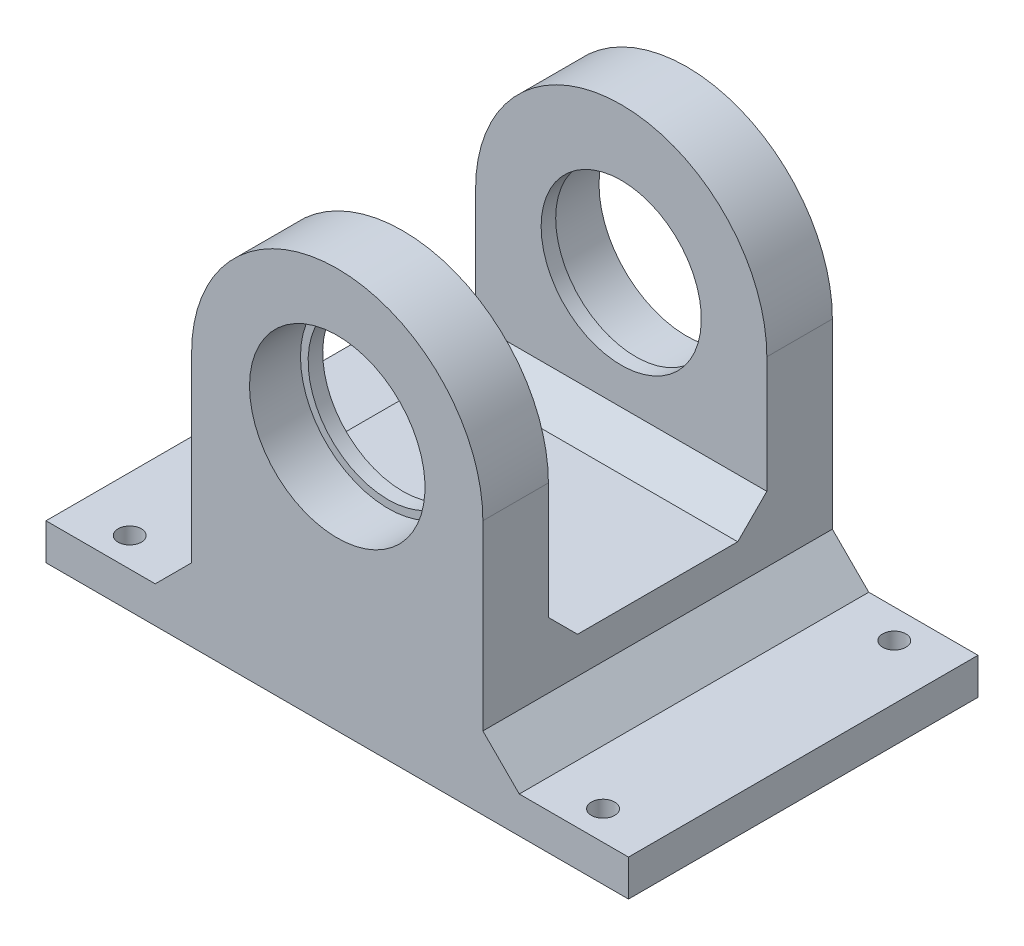
SolidWorks part; units mm, degrees
material "6061 合金"
ref_plane "前视基准面" through (0, 0, 0) normal (0, 0, 1) x (1, 0, 0)
ref_plane "上视基准面" through (0, 0, 0) normal (0, 1, 0) x (1, 0, 0)
ref_plane "右视基准面" through (0, 0, 0) normal (1, 0, 0) x (0, 0, -1)
sketch "草图1" plane through (0, 0, 0) normal (0, 0, 1) x (1, 0, 0)
  line L0 (-20, -35) -> (-20, 0)
  line L3 (-20, -35) -> (20, -35)
  line L7 (20, -35) -> (20, 0)
  arc A0 (20, 0) -> (-20, 0) centre (0, 0) ccw
  circle A1 centre (0, 0) radius 11
  dimension "D2" = 40
  dimension "D3" = 40
  dimension "D4" = 22
  dimension "D1" = 35
extrude "凸台-拉伸1" add sketch "草图1" along normal mid plane 48
sketch "草图2" plane through (0, 0, 0) normal (1, 0, 0) x (0, 0, -1)
  line L0 (-24, 0) -> (24, 0) construction
  line L1 (0, 13.255) -> (0, -13.255) construction
  line L2 (-24, -35) -> (24, -35) construction
  line L4 (-15, 49.95) -> (15, 49.95)
  line L5 (-15, 49.95) -> (-15, -20)
  line L6 (-15, -20) -> (15, -20)
  line L7 (15, 49.95) -> (15, -20)
  line L14 (-30, -20) -> (0, -35) construction
  point P6 (-30, 4.975)
  dimension "D1" = 30
  dimension "D2" = 20
  dimension "D3" = 15
extrude "切除-拉伸1" cut sketch "草图2" against normal through all both and the other way through all
sketch "草图4" plane through (0, 0, -24) normal (0, 0, -1) x (-1, 0, 0)
  circle A0 centre (0, 0) radius 12.05
  dimension "D1" = 24.1
extrude "切除-拉伸3" cut sketch "草图4" against normal blind 7
chamfer "倒角2" distance 4 angle 45 2 edges at (0, -20, -15) (0, -20, 15)
mirror "镜向1" about plane through (0, 0, 0) normal (0, 0, 1) of "切除-拉伸3"
sketch "草图5" plane through (-20, 0, 0) normal (-1, 0, 0) x (0, 0, 1)
  line L0 (0, -20) -> (0, -35) construction
  line L1 (11, -20) -> (-11, -20) construction
  line L2 (24, -35) -> (-24, -35) construction
  line L4 (-24, 0) -> (-24, -35) construction
  line L7 (-24, -35) -> (24, -35)
  line L8 (-24, -35) -> (-24, -30)
  line L9 (-24, -30) -> (24, -30)
  line L10 (24, -35) -> (24, -30)
  line L11 (-24, -35) -> (24, -30) construction
  line L12 (-24, -30) -> (24, -35) construction
  point P12 (0, -32.5)
  dimension "D1" = 5
extrude "凸台-拉伸2" add sketch "草图5" along normal blind 20
ref_plane "基准面1" through (0, 0, 0) normal (-1, 0, 0) x (0, 0, 1)
mirror "镜向2" about plane through (0, 0, 0) normal (-1, 0, 0) of "凸台-拉伸2"
chamfer "倒角3" distance 5 distance2 5 2 edges at (20, -30, 0) (-20, -30, 0)
sketch "草图6" plane through (0, -35, 0) normal (0, -1, 0) x (1, 0, 0)
  line L0 (0, -24) -> (0, 24) construction
  line L1 (-40, -24) -> (40, -24) construction
  line L2 (-40, 24) -> (40, 24) construction
  line L3 (40, 0) -> (-40, 0) construction
  line L4 (40, -24) -> (40, 24) construction
  line L5 (-40, -24) -> (-40, 24) construction
  circle A0 centre (32.5, -20) radius 1.6
  circle A1 centre (-32.5, -20) radius 1.6
  circle A2 centre (-32.5, 20) radius 1.6
  circle A3 centre (32.5, 20) radius 1.6
  dimension "D1" = 40
  dimension "D2" = 65
extrude "切除-拉伸4" cut sketch "草图6" against normal through all
